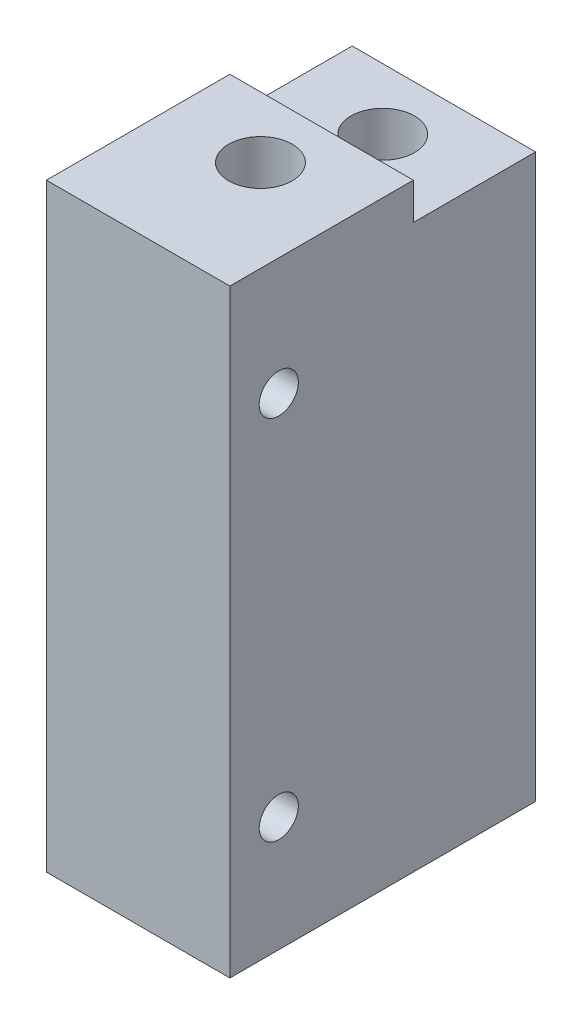
SolidWorks part; units mm, degrees
ref_plane "Front Plane" through (0, 0, 0) normal (0, 0, 1) x (1, 0, 0)
ref_plane "Top Plane" through (0, 0, 0) normal (0, 1, 0) x (1, 0, 0)
ref_plane "Right Plane" through (0, 0, 0) normal (1, 0, 0) x (0, 0, -1)
sketch "Sketch1" plane through (0, 0, 0) normal (1, 0, 0) x (0, 0, -1)
  line L0 (-11, 49) -> (-11, 0) construction
  line L1 (0, 0) -> (-15, 0)
  line L2 (0, 0) -> (0, 49)
  line L3 (0, 49) -> (-15, 49)
  line L4 (-15, 0) -> (-15, 49)
  line L5 (-11, 39.6) -> (-11, 9.6) construction
  circle A0 centre (-11, 39.6) radius 1.6
  circle A1 centre (-11, 9.6) radius 1.6
  dimension "D4" = 3.2
  dimension "D5" = 30
  dimension "D6" = 9.6
  dimension "D1" = 15
  dimension "D2" = 49
  dimension "D3" = 11
extrude "Boss-Extrude1" add sketch "Sketch1" along normal blind 15
sketch "Sketch2" plane through (0, 0, 0) normal (0, -1, 0) x (1, 0, 0)
  line L0 (0, 5) -> (15, 5) construction
  line L1 (0, 15) -> (0, 0) construction
  line L2 (15, 15) -> (15, 0) construction
  line L4 (15, 0) -> (0, 0) construction
  circle A2 centre (7.5, 5) radius 2.6
  dimension "D1" = 5.2
  dimension "D5" = 5
extrude "Cut-Extrude1" cut sketch "Sketch2" against normal through all
sketch "Sketch5" plane through (0, 0, 0) normal (0, 0, -1) x (-1, 0, 0)
  line L0 (0, 0) -> (0, 49) construction
  line L1 (-15, 49) -> (0, 49)
  line L2 (-15, 49) -> (-15, 3)
  line L3 (-15, 3) -> (0, 3)
  line L4 (0, 49) -> (0, 3)
  dimension "D1" = 46
extrude "Boss-Extrude3" add sketch "Sketch5" along normal blind 10
sketch "Sketch6" plane through (0, 3, 0) normal (0, -1, 0) x (1, 0, 0)
  line L0 (7.5, 5) -> (7.5, -10) construction
  line L1 (15, -10) -> (0, -10) construction
  circle A0 centre (7.5, -5) radius 2.6
  circle A1 centre (7.5, 5) radius 2.6 construction
  dimension "D1" = 5.2
  dimension "D2" = 10
extrude "Cut-Extrude2" cut sketch "Sketch6" against normal through all
mirror "Mirror1" about plane through (15, 49, 0) normal (0, -1, 0) of bodies 105
sketch "Sketch7" plane through (0, 0, 0) normal (0, -1, 0) x (1, 0, 0)
  line L1 (0, 15) -> (15, 15)
  line L2 (0, 15) -> (0, -10)
  line L3 (0, -10) -> (15, -10)
  line L4 (15, 15) -> (15, -10)
extrude "Cut-Extrude3" cut sketch "Sketch7" against normal blind 49
